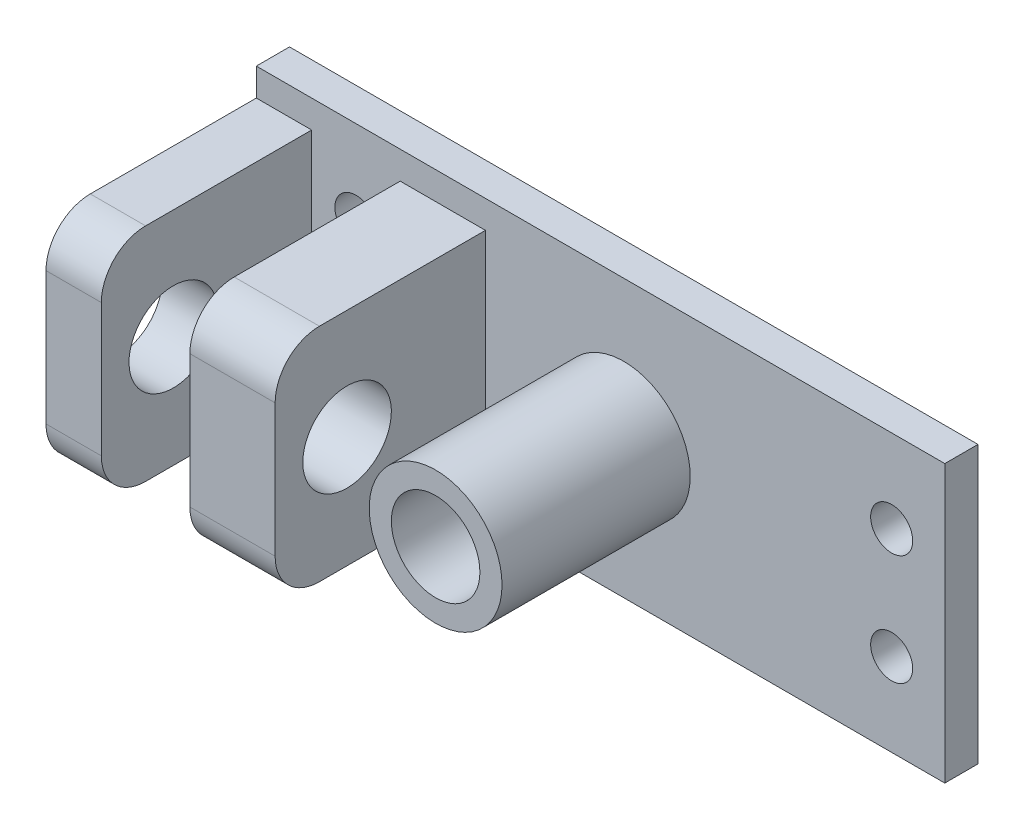
SolidWorks part; units mm, degrees
ref_plane "Front Plane" through (0, 0, 0) normal (0, 0, 1) x (1, 0, 0)
ref_plane "Top Plane" through (0, 0, 0) normal (0, 1, 0) x (1, 0, 0)
ref_plane "Right Plane" through (0, 0, 0) normal (1, 0, 0) x (0, 0, -1)
sketch "Sketch1" plane through (0, 0, 0) normal (0, 0, 1) x (1, 0, 0)
  line L0 (-35.6557, 0) -> (35.5199, 0) construction
  line L1 (-29, 12.5) -> (29, 12.5)
  line L2 (-29, 12.5) -> (-29, -12.5)
  line L3 (-29, -12.5) -> (29, -12.5)
  line L4 (29, 12.5) -> (29, -12.5)
  line L5 (-29, 12.5) -> (29, -12.5) construction
  line L6 (-29, -12.5) -> (29, 12.5) construction
  line L7 (0, 14.8056) -> (0, -17.7939) construction
  circle A0 centre (24.2, 5) radius 1.9
  circle A1 centre (24.2, -5) radius 1.9
  circle A2 centre (-24.2, 5) radius 1.9
  circle A3 centre (-24.2, -5) radius 1.9
  point P0 (0, 0)
  point P16 (0, 0)
  point P19 (0, 0)
  point P20 (0, 0)
  point P21 (0, 0)
  point P22 (0, 0)
  point P23 (0, 0)
  dimension "D3" = 3.8
  dimension "D4" = 3.8
  dimension "D7" = 3.8
  dimension "D8" = 3.8
  dimension "D1" = 58
  dimension "D2" = 25
  dimension "D5" = 10
  dimension "D6" = 5
  dimension "D10" = 24.2
extrude "Boss-Extrude1" add sketch "Sketch1" along normal blind 3
sketch "Sketch2" plane through (0, 0, 0) normal (0, 0, 1) x (1, 0, 0)
  line L0 (-31.697, 0) -> (34.595, 0) construction
  line L1 (0, 15.9391) -> (0, -16.084) construction
  circle A0 centre (0, 0) radius 6
  point P7 (0, 0)
  dimension "D1" = 12
extrude "Boss-Extrude2" add sketch "Sketch2" along normal blind 20
sketch "Sketch3" plane through (0, 0, 20) normal (0, 0, 1) x (1, 0, 0)
  line L0 (0, 15.1421) -> (0, -15.287) construction
  line L1 (-31.4072, 0) -> (31.8419, 0) construction
  circle A0 centre (0, 0) radius 4
  dimension "D1" = 8
extrude "Cut-Extrude1" cut sketch "Sketch3" against normal through all
sketch "Sketch4" plane through (0, 0, 3) normal (0, 0, 1) x (1, 0, 0)
  line L0 (-32.2766, 0) -> (-1.7026, 0) construction
  line L1 (0, 15.8445) -> (0, -16.1506) construction
  line L2 (-20.2, 9.9981) -> (-12.5, 9.9981)
  line L3 (-20.2, 9.9981) -> (-20.2, -9.9981)
  line L4 (-20.2, -9.9981) -> (-12.5, -9.9981)
  line L5 (-12.5, 9.9981) -> (-12.5, -9.9981)
  line L6 (-20.2, 9.9981) -> (-12.5, -9.9981) construction
  line L7 (-20.2, -9.9981) -> (-12.5, 9.9981) construction
  point P3 (-16.35, 0)
  dimension "D1" = 12.5
extrude "Boss-Extrude3" add sketch "Sketch4" along normal blind 19
sketch "Sketch5" plane through (-20.2, 0, 0) normal (-1, 0, 0) x (0, 0, 1)
  line L0 (-1.6546, 0) -> (24.695, 0) construction
  line L1 (15.5, 11.5987) -> (15.5, -11.437) construction
  line L2 (3, 9.9981) -> (3, -9.9981) construction
  circle A0 centre (15.5, 0.0808) radius 4
  dimension "D1" = 8
  dimension "D2" = 12.5
extrude "Cut-Extrude2" cut sketch "Sketch5" against normal up to next
fillet "Fillet1" radius 4 2 edges at (-16.35, -9.9981, 22) (-16.35, 9.9981, 22)
sketch "Sketch7" plane through (0, 0, 3) normal (0, 0, 1) x (1, 0, 0)
  line L0 (-29, -12.5) -> (29, -12.5) construction
  line L1 (-29, 12.5) -> (-33.2, 12.5)
  line L2 (-29, 12.5) -> (-29, -12.5)
  line L3 (-29, -12.5) -> (-33.2, -12.5)
  line L4 (-33.2, 12.5) -> (-33.2, -12.5)
  line L6 (-20.2, 5.9981) -> (-20.2, -5.9981) construction
  dimension "D1" = 13
extrude "Boss-Extrude4" add sketch "Sketch7" against normal blind 3
sketch "Sketch8" plane through (0, 0, 3) normal (0, 0, 1) x (1, 0, 0)
  line L1 (-28.2, 9.9981) -> (-33.2, 9.9981)
  line L2 (-28.2, 9.9981) -> (-28.2, -9.9981)
  line L3 (-28.2, -9.9981) -> (-33.2, -9.9981)
  line L4 (-33.2, 9.9981) -> (-33.2, -9.9981)
  line L5 (-20.2, -9.9981) -> (-12.5, -9.9981) construction
  line L7 (-12.5, 9.9981) -> (-20.2, 9.9981) construction
  dimension "D2" = 5
extrude "Boss-Extrude5" add sketch "Sketch8" along normal blind 19
sketch "Sketch9" plane through (-28.2, 0, 0) normal (1, 0, 0) x (0, 0, -1)
  line L0 (-20.1823, 0) -> (-11.5543, 0) construction
  line L1 (-15.5, 4.3115) -> (-15.5, -4.1843) construction
  circle A0 centre (-15.5, 0.0636) radius 4
  dimension "D1" = 8
extrude "Cut-Extrude3" cut sketch "Sketch9" against normal up to next
fillet "Fillet2" radius 4 2 edges at (-30.7, -9.9981, 22) (-30.7, 9.9981, 22)
